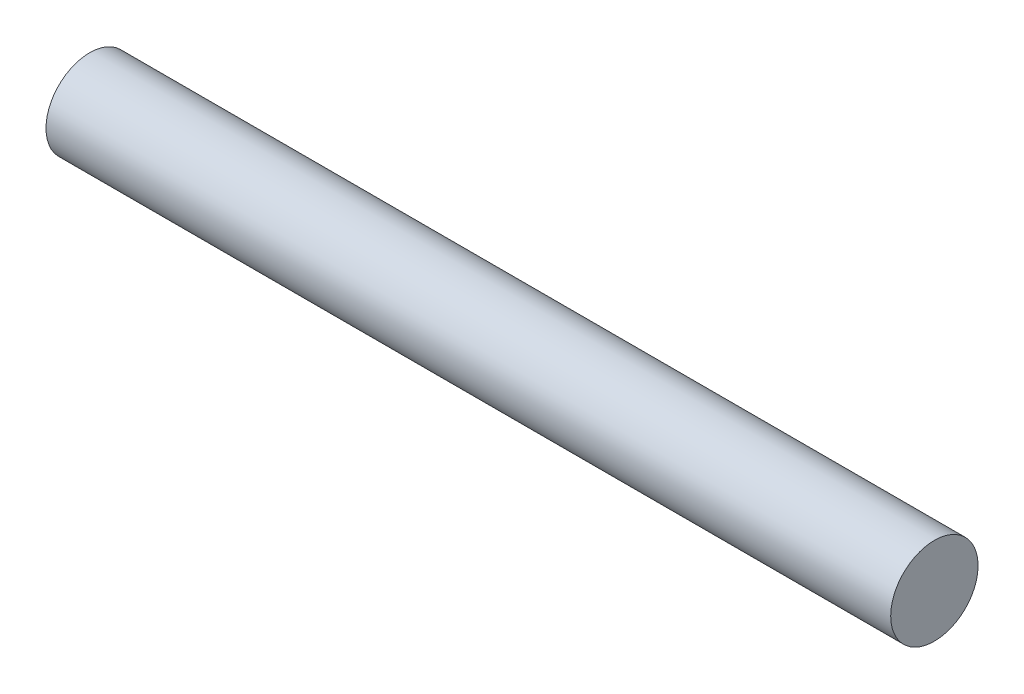
SolidWorks part; units mm, degrees
material "Cast Alloy Steel"
ref_plane "Front Plane" through (0, 0, 0) normal (0, 0, 1) x (1, 0, 0)
ref_plane "Top Plane" through (0, 0, 0) normal (0, 1, 0) x (1, 0, 0)
ref_plane "Right Plane" through (0, 0, 0) normal (1, 0, 0) x (0, 0, -1)
sketch "Sketch1" plane through (0, 0, 0) normal (1, 0, 0) x (0, 0, -1)
  circle A0 centre (0, 0) radius 1.5
  dimension "D1" = 3
extrude "Boss-Extrude2" add sketch "Sketch1" along normal blind 29
cosmetic thread "Cosmetic Thread6" parameters "D1"=29, "D2"=2.439
cosmetic thread "Cosmetic Thread7" parameters "D1"=29, "D2"=2.439
